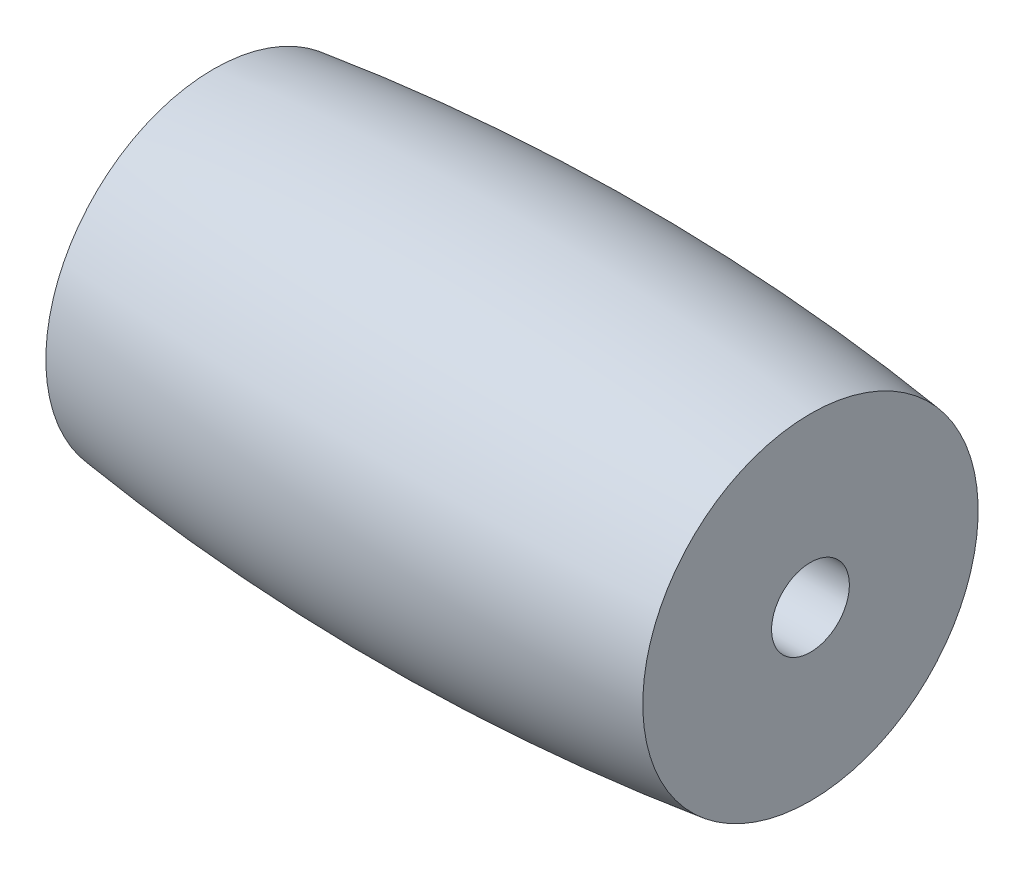
SolidWorks part; units mm, degrees
ref_plane "Front Plane" through (0, 0, 0) normal (0, 0, 1) x (1, 0, 0)
ref_plane "Top Plane" through (0, 0, 0) normal (0, 1, 0) x (1, 0, 0)
ref_plane "Right Plane" through (0, 0, 0) normal (1, 0, 0) x (0, 0, -1)
sketch "Sketch2" plane through (0, 0, 0) normal (0, 0, 1) x (1, 0, 0)
  line L1 (5.6515, 0.7366) -> (5.6515, 3.175)
  line L2 (-5.6515, 0.7366) -> (-5.6515, 3.175)
  line L3 (0, 0) -> (-9.3956, 0) construction
  line L4 (-5.6515, 0.7366) -> (5.6515, 0.7366)
  arc A0 (-5.6515, 3.175) -> (5.6515, 3.175) centre (0, -41.5564) cw
  point P3 (0, 0.7366)
  point P4 (0, 0)
  point P10 (0, 3.5306)
  dimension "D1" = 11.303
  dimension "D2" = 7.0612
  dimension "D3" = 6.35
  dimension "D4" = 1.4732
revolve "Revolve1" add sketch "Sketch2" angle 360 about L3
